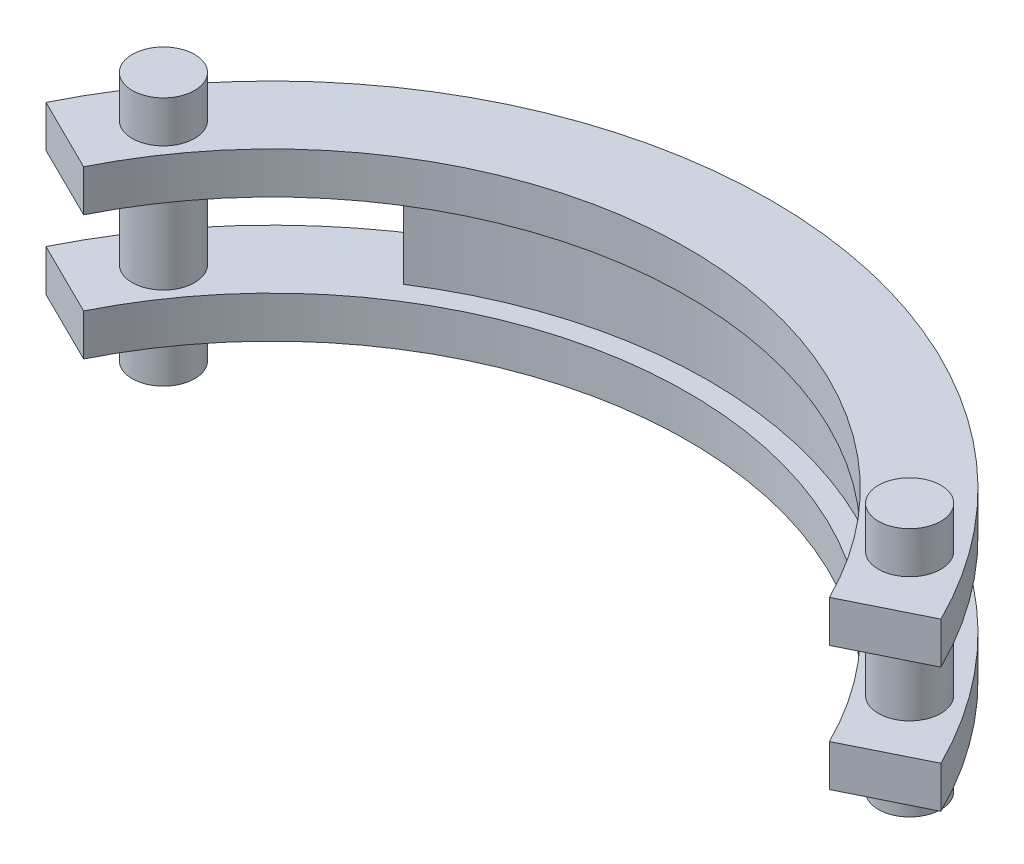
SolidWorks part; units mm, degrees
ref_plane "Front Plane" through (0, 0, 0) normal (0, 0, 1) x (1, 0, 0)
ref_plane "Top Plane" through (0, 0, 0) normal (0, 1, 0) x (1, 0, 0)
ref_plane "Right Plane" through (0, 0, 0) normal (1, 0, 0) x (0, 0, -1)
sketch "Sketch1" plane through (0, 0, 0) normal (0, 1, 0) x (1, 0, 0)
  line L0 (-107.5297, 53.267) -> (-89.608, 44.3892)
  line L1 (88.7289, 46.1214) -> (106.4746, 55.3457)
  arc A0 (-89.608, 44.3892) -> (88.7289, 46.1214) centre (0, 0) cw
  arc A1 (-107.5297, 53.267) -> (106.4746, 55.3457) centre (0, 0) cw
  dimension "D1" = 100
  dimension "D2" = 20
extrude "Boss-Extrude1" add sketch "Sketch1" along normal blind 10
sketch "Sketch2" plane through (0, 10, 0) normal (0, 1, 0) x (1, 0, 0)
  line L5 (-62.0973, 96.7932) -> (-56.6975, 88.3764)
  line L6 (0, 0) -> (0, 28.0551) construction
  line L7 (90.7536, 52.809) -> (99.6356, 57.4259)
  line L8 (-100.7323, 55.4797) -> (-91.7623, 51.0362)
  line L11 (62.0973, 96.7932) -> (56.6975, 88.3764)
  arc A10 (90.7536, 52.809) -> (-91.7623, 51.0362) centre (0, 0) ccw
  arc A11 (99.6356, 57.4259) -> (-100.7323, 55.4797) centre (0, 0) ccw
  arc A12 (56.6975, 88.3764) -> (-56.6975, 88.3764) centre (0, 0) ccw
  arc A13 (62.0973, 96.7932) -> (-62.0973, 96.7932) centre (0, 0) ccw
  dimension "D1" = 5
extrude "Boss-Extrude2" add sketch "Sketch2" along normal blind 10
mirror "Mirror1" about plane through (0, 20, 0) normal (0, 1, 0) of bodies 102
sketch "Sketch3" plane through (0, 0, 0) normal (0, -1, 0) x (1, 0, 0)
  circle A0 centre (-89.6581, -63.6162) radius 7.5
  dimension "D1" = 15
extrude "Boss-Extrude3" add sketch "Sketch3" along normal blind 10 and the other way blind 50
mirror "Mirror2" about plane through (0, 0, 0) normal (1, 0, 0) of bodies 104
